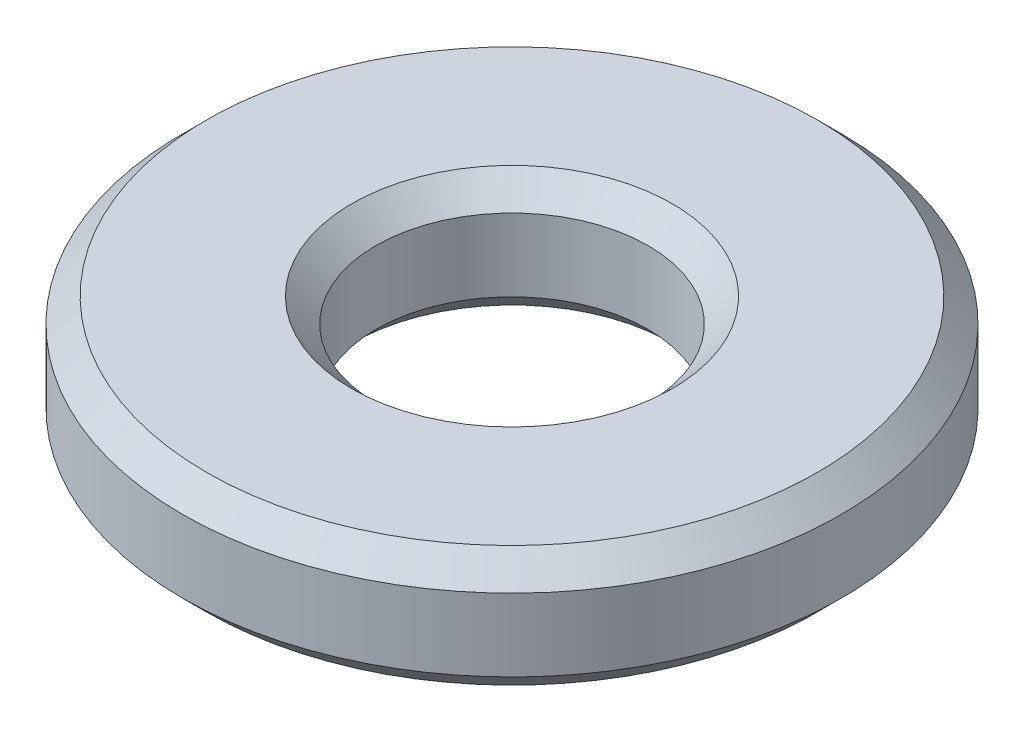
SolidWorks part; units mm, degrees
ref_plane "Front Plane" through (0, 0, 0) normal (0, 0, 1) x (1, 0, 0)
ref_plane "Top Plane" through (0, 0, 0) normal (0, 1, 0) x (1, 0, 0)
ref_plane "Right Plane" through (0, 0, 0) normal (1, 0, 0) x (0, 0, -1)
sketch "Sketch2" plane through (0, 0, 0) normal (0, 1, 0) x (1, 0, 0)
  circle A0 centre (0, 0) radius 2.25
  circle A1 centre (0, 0) radius 5.45
  dimension "D1" = 3.2
  dimension "D2" = 4.5
extrude "Boss-Extrude1" add sketch "Sketch2" along normal blind 2
chamfer "Chamfer1" distance 0.4 angle 45 4 edges at (0, 0, 5.45) (0, 0, 2.25) (0, 2, 5.45) (0, 2, 2.25)
